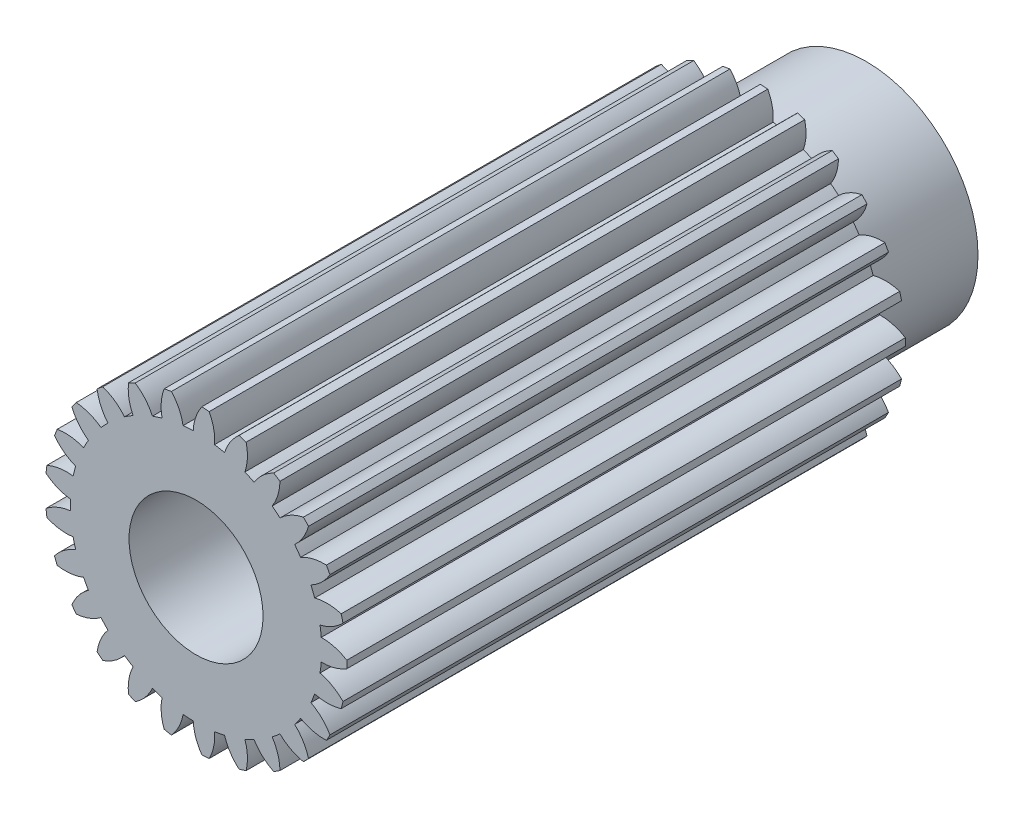
SolidWorks part; units mm, degrees
ref_plane "前视基准面" through (0, 0, 0) normal (0, 0, 1) x (1, 0, 0)
ref_plane "上视基准面" through (0, 0, 0) normal (0, 1, 0) x (1, 0, 0)
ref_plane "右视基准面" through (0, 0, 0) normal (1, 0, 0) x (0, 0, -1)
other "Configuration Table"
sketch "草图1" plane through (0, 0, 0) normal (0, 0, 1) x (1, 0, 0)
  line L0 (0, 0) -> (0, 10.2399) construction
  line L1 (0, 0) -> (0.6639, 10.5517) construction
  line L2 (0, 0) -> (3.8338, 10.5332) construction
  line L3 (0, 6.25) -> (2.0087, 5.5189) construction
  circle A0 centre (0, 0) radius 6.25 construction
  arc A1 (-0.1263, 5.6236) -> (-0.5795, 5.5951) centre (0, 0) ccw
  arc A2 (0.5897, 6.7242) -> (0.2577, 6.7451) centre (0, 0) ccw
  arc A3 (0.2577, 6.7451) -> (-0.1263, 5.6236) centre (2.0087, 5.5189) ccw
  arc A4 (0.5897, 6.7242) -> (0.8302, 5.5634) centre (-1.3012, 5.7271) cw
  arc A5 (2.2434, 6.3663) -> (2.1877, 5.1822) centre (0.164, 5.8708) cw
  arc A6 (2.2434, 6.3663) -> (1.9271, 6.4691) centre (0, 0) ccw
  arc A7 (1.9271, 6.4691) -> (1.2761, 5.4783) centre (3.3181, 4.846) ccw
  arc A8 (3.7561, 5.6084) -> (3.4077, 4.4753) centre (1.6188, 5.6456) cw
  arc A9 (3.7561, 5.6084) -> (3.4753, 5.7866) centre (0, 0) ccw
  arc A10 (3.4753, 5.7866) -> (2.5985, 4.9889) centre (4.419, 3.8685) ccw
  arc A11 (5.0329, 4.4981) -> (4.4136, 3.4873) centre (2.972, 5.0656) cw
  arc A12 (5.0329, 4.4981) -> (4.8052, 4.7405) centre (0, 0) ccw
  arc A13 (4.8052, 4.7405) -> (3.7575, 4.1859) centre (5.2422, 2.648) ccw
  arc A14 (5.9934, 3.1051) -> (5.1422, 2.2801) centre (4.1384, 4.1674) cw
  arc A15 (5.9934, 3.1051) -> (5.8332, 3.3966) centre (0, 0) ccw
  arc A16 (5.8332, 3.3966) -> (4.6804, 3.1199) centre (5.7361, 1.2612) ccw
  arc A17 (6.5773, 1.5171) -> (5.5476, 0.9296) centre (5.0447, 3.0073) cw
  arc A18 (6.5773, 1.5171) -> (6.4946, 1.8392) centre (0, 0) ccw
  arc A19 (6.4946, 1.8392) -> (5.3093, 1.8579) centre (5.8695, -0.205) ccw
  arc A20 (6.748, -0.1663) -> (5.6046, -0.4792) centre (5.6341, 1.6582) cw
  arc A21 (6.748, -0.1663) -> (6.748, 0.1663) centre (0, 0) ccw
  arc A22 (6.748, 0.1663) -> (5.6046, 0.4792) centre (5.6341, -1.6582) ccw
  arc A23 (6.4946, -1.8392) -> (5.3093, -1.8579) centre (5.8695, 0.205) cw
  arc A24 (6.4946, -1.8392) -> (6.5773, -1.5171) centre (0, 0) ccw
  arc A25 (6.5773, -1.5171) -> (5.5476, -0.9296) centre (5.0447, -3.0073) ccw
  arc A26 (5.8332, -3.3966) -> (4.6804, -3.1199) centre (5.7361, -1.2612) cw
  arc A27 (5.8332, -3.3966) -> (5.9934, -3.1051) centre (0, 0) ccw
  arc A28 (5.9934, -3.1051) -> (5.1422, -2.2801) centre (4.1384, -4.1674) ccw
  arc A29 (4.8052, -4.7405) -> (3.7575, -4.1859) centre (5.2422, -2.648) cw
  arc A30 (4.8052, -4.7405) -> (5.0329, -4.4981) centre (0, 0) ccw
  arc A31 (5.0329, -4.4981) -> (4.4136, -3.4873) centre (2.972, -5.0656) ccw
  arc A32 (3.4753, -5.7866) -> (2.5985, -4.9889) centre (4.419, -3.8685) cw
  arc A33 (3.4753, -5.7866) -> (3.7561, -5.6084) centre (0, 0) ccw
  arc A34 (3.7561, -5.6084) -> (3.4077, -4.4753) centre (1.6188, -5.6456) ccw
  arc A35 (1.9271, -6.4691) -> (1.2761, -5.4783) centre (3.3181, -4.846) cw
  arc A36 (1.9271, -6.4691) -> (2.2434, -6.3663) centre (0, 0) ccw
  arc A37 (2.2434, -6.3663) -> (2.1877, -5.1822) centre (0.164, -5.8708) ccw
  arc A38 (0.2577, -6.7451) -> (-0.1263, -5.6236) centre (2.0087, -5.5189) cw
  arc A39 (0.2577, -6.7451) -> (0.5897, -6.7242) centre (0, 0) ccw
  arc A40 (0.5897, -6.7242) -> (0.8302, -5.5634) centre (-1.3012, -5.7271) ccw
  arc A41 (-1.4278, -6.5973) -> (-1.5209, -5.4155) centre (0.5731, -5.845) cw
  arc A42 (-1.4278, -6.5973) -> (-1.1011, -6.6596) centre (0, 0) ccw
  arc A43 (-1.1011, -6.6596) -> (-0.5795, -5.5951) centre (-2.6846, -5.2236) ccw
  arc A44 (-3.0236, -6.0349) -> (-2.8199, -4.8671) centre (-0.8985, -5.8039) cw
  arc A45 (-3.0236, -6.0349) -> (-2.7227, -6.1765) centre (0, 0) ccw
  arc A46 (-2.7227, -6.1765) -> (-1.9527, -5.2752) centre (-3.8993, -4.3919) ccw
  arc A47 (-4.4294, -5.0934) -> (-3.9417, -4.0129) centre (-2.3137, -5.3982) cw
  arc A48 (-4.4294, -5.0934) -> (-4.1732, -5.3054) centre (0, 0) ccw
  arc A49 (-4.1732, -5.3054) -> (-3.2032, -4.6238) centre (-4.869, -3.2842) ccw
  arc A50 (-5.557, -3.8318) -> (-4.8158, -2.9066) centre (-3.5834, -4.6532) cw
  arc A51 (-5.557, -3.8318) -> (-5.3615, -4.1009) centre (0, 0) ccw
  arc A52 (-5.3615, -4.1009) -> (-4.2525, -3.682) centre (-5.5328, -1.9701) ccw
  arc A53 (-6.3353, -2.3295) -> (-5.3874, -1.6176) centre (-4.628, -3.6158) cw
  arc A54 (-6.3353, -2.3295) -> (-6.2129, -2.6387) centre (0, 0) ccw
  arc A55 (-6.2129, -2.6387) -> (-5.0346, -2.5087) centre (-5.8489, -0.5323) ccw
  arc A56 (-6.7156, -0.6808) -> (-5.6204, -0.227) centre (-5.3819, -2.3513) cw
  arc A57 (-6.7156, -0.6808) -> (-6.6739, -1.0107) centre (0, 0) ccw
  arc A58 (-6.6739, -1.0107) -> (-5.5003, -1.1779) centre (-5.7975, 0.939) ccw
  arc A59 (-6.6739, 1.0107) -> (-5.5003, 1.1779) centre (-5.7975, -0.939) cw
  arc A60 (-6.6739, 1.0107) -> (-6.7156, 0.6808) centre (0, 0) ccw
  arc A61 (-6.7156, 0.6808) -> (-5.6204, 0.227) centre (-5.3819, 2.3513) ccw
  arc A62 (-6.2129, 2.6387) -> (-5.0346, 2.5087) centre (-5.8489, 0.5323) cw
  arc A63 (-6.2129, 2.6387) -> (-6.3353, 2.3295) centre (0, 0) ccw
  arc A64 (-6.3353, 2.3295) -> (-5.3874, 1.6176) centre (-4.628, 3.6158) ccw
  arc A65 (-5.3615, 4.1009) -> (-4.2525, 3.682) centre (-5.5328, 1.9701) cw
  arc A66 (-5.3615, 4.1009) -> (-5.557, 3.8318) centre (0, 0) ccw
  arc A67 (-5.557, 3.8318) -> (-4.8158, 2.9066) centre (-3.5834, 4.6532) ccw
  arc A68 (-4.1732, 5.3054) -> (-3.2032, 4.6238) centre (-4.869, 3.2842) cw
  arc A69 (-4.1732, 5.3054) -> (-4.4294, 5.0934) centre (0, 0) ccw
  arc A70 (-4.4294, 5.0934) -> (-3.9417, 4.0129) centre (-2.3137, 5.3982) ccw
  arc A71 (-2.7227, 6.1765) -> (-1.9527, 5.2752) centre (-3.8993, 4.3919) cw
  arc A72 (-2.7227, 6.1765) -> (-3.0236, 6.0349) centre (0, 0) ccw
  arc A73 (-3.0236, 6.0349) -> (-2.8199, 4.8671) centre (-0.8985, 5.8039) ccw
  arc A74 (-1.1011, 6.6596) -> (-0.5795, 5.5951) centre (-2.6846, 5.2236) cw
  arc A75 (-1.1011, 6.6596) -> (-1.4278, 6.5973) centre (0, 0) ccw
  arc A76 (-1.4278, 6.5973) -> (-1.5209, 5.4155) centre (0.5731, 5.845) ccw
  arc A77 (1.2761, 5.4783) -> (0.8302, 5.5634) centre (0, 0) ccw
  arc A78 (2.5985, 4.9889) -> (2.1877, 5.1822) centre (0, 0) ccw
  arc A79 (3.7575, 4.1859) -> (3.4077, 4.4753) centre (0, 0) ccw
  arc A80 (5.3093, 1.8579) -> (5.1422, 2.2801) centre (0, 0) ccw
  arc A81 (5.6046, 0.4792) -> (5.5476, 0.9296) centre (0, 0) ccw
  arc A82 (4.6804, 3.1199) -> (4.4136, 3.4873) centre (0, 0) ccw
  arc A83 (5.5476, -0.9296) -> (5.6046, -0.4792) centre (0, 0) ccw
  arc A84 (5.1422, -2.2801) -> (5.3093, -1.8579) centre (0, 0) ccw
  arc A85 (4.4136, -3.4873) -> (4.6804, -3.1199) centre (0, 0) ccw
  arc A86 (3.4077, -4.4753) -> (3.7575, -4.1859) centre (0, 0) ccw
  arc A87 (2.1877, -5.1822) -> (2.5985, -4.9889) centre (0, 0) ccw
  arc A88 (0.8302, -5.5634) -> (1.2761, -5.4783) centre (0, 0) ccw
  arc A89 (-0.5795, -5.5951) -> (-0.1263, -5.6236) centre (0, 0) ccw
  arc A90 (-1.9527, -5.2752) -> (-1.5209, -5.4155) centre (0, 0) ccw
  arc A91 (-3.2032, -4.6238) -> (-2.8199, -4.8671) centre (0, 0) ccw
  arc A92 (-4.2525, -3.682) -> (-3.9417, -4.0129) centre (0, 0) ccw
  arc A93 (-5.0346, -2.5087) -> (-4.8158, -2.9066) centre (0, 0) ccw
  arc A94 (-5.5003, -1.1779) -> (-5.3874, -1.6176) centre (0, 0) ccw
  arc A95 (-5.6204, 0.227) -> (-5.6204, -0.227) centre (0, 0) ccw
  arc A96 (-5.3874, 1.6176) -> (-5.5003, 1.1779) centre (0, 0) ccw
  arc A97 (-4.8158, 2.9066) -> (-5.0346, 2.5087) centre (0, 0) ccw
  arc A98 (-3.9417, 4.0129) -> (-4.2525, 3.682) centre (0, 0) ccw
  arc A99 (-2.8199, 4.8671) -> (-3.2032, 4.6238) centre (0, 0) ccw
  arc A100 (-1.5209, 5.4155) -> (-1.9527, 5.2752) centre (0, 0) ccw
  point P160 (0, 0)
  dimension "D1" = 12.5
  dimension "D2" = 13.5
  dimension "D3" = 11.25
  dimension "D4" = 3.6
  dimension "D5" = 20
  dimension "D6" = 25
extrude "凸台-拉伸1" add sketch "草图1" along normal blind 25
sketch "草图2" plane through (0, 0, 0) normal (0, 0, -1) x (-1, 0, 0)
  circle A0 centre (0, 0) radius 5
  circle A1 centre (0, 0) radius 2.75
  dimension "D1" = 10
  dimension "D2" = 5.5
extrude "凸台-拉伸2" add sketch "草图2" along normal blind 5
sketch "草图3" plane through (0, 0, 0) normal (0, 0, -1) x (-1, 0, 0)
  circle A0 centre (0, 0) radius 3
extrude "凸台-拉伸3" add sketch "草图3" along normal blind 1.5
sketch "草图4" plane through (0, 0, 25) normal (0, 0, 1) x (1, 0, 0)
  circle A0 centre (0, 0) radius 3
extrude "切除-拉伸1" cut sketch "草图4" against normal offset from surface (23.5 mm away) 3 up to face at (-2.75, 0, -1.5)
sketch "草图5" plane through (0, 0, 1.5) normal (0, 0, 1) x (1, 0, 0)
  circle A0 centre (0, 0) radius 1.6
extrude "切除-拉伸2" cut sketch "草图5" against normal through all
